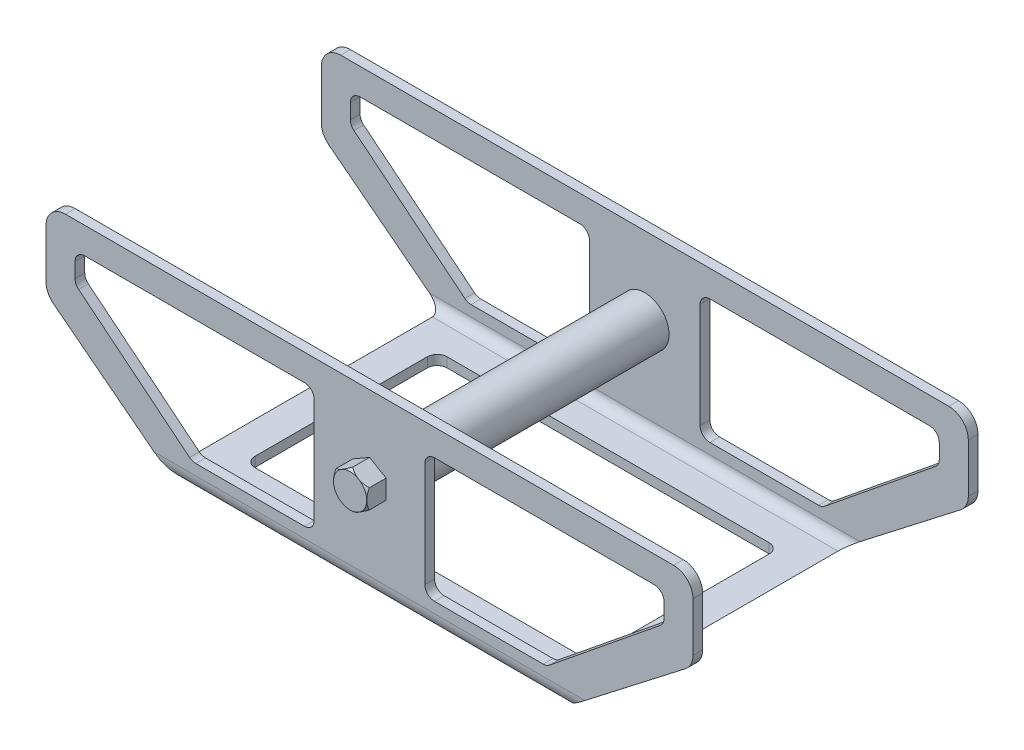
SolidWorks part; units mm, degrees
ref_plane "Front Plane" through (0, 0, 0) normal (0, 0, 1) x (1, 0, 0)
ref_plane "Top Plane" through (0, 0, 0) normal (0, 1, 0) x (1, 0, 0)
ref_plane "Right Plane" through (0, 0, 0) normal (1, 0, 0) x (0, 0, -1)
sketch "Sketch1" plane through (0, 0, 0) normal (0, 0, 1) x (1, 0, 0)
  line L0 (0, -413.3583) -> (0, 413.3583) construction
  line L1 (-333.43, 0) -> (333.43, 0)
  line L2 (333.43, 0) -> (333.43, -80.23)
  line L3 (333.43, -80.23) -> (196.11, -186.5035)
  line L4 (196.11, -186.5035) -> (-196.11, -186.5035)
  line L5 (-333.43, 0) -> (-333.43, -80.23)
  line L6 (-333.43, -80.23) -> (-196.11, -186.5035)
  point P13 (0, 0)
  point P15 (0, -186.5035)
  dimension "D1" = 333.43
  dimension "D2" = 80.23
  dimension "D3" = 173.64
  dimension "D4" = 196.11
extrude "Boss-Extrude1" add sketch "Sketch1" along normal mid plane 293.75
sketch "Sketch2" plane through (333.43, 0, 0) normal (1, 0, 0) x (0, 0, -1)
  line L0 (-146.875, -186.5035) -> (146.875, -186.5035) construction
  line L1 (-136.875, 36.7584) -> (136.875, 36.7584)
  line L2 (-136.875, 36.7584) -> (-136.875, -176.5035)
  line L3 (-136.875, -176.5035) -> (136.875, -176.5035)
  line L4 (136.875, 36.7584) -> (136.875, -176.5035)
  line L5 (-146.875, -186.5035) -> (-146.875, -80.23) construction
  line L6 (146.875, -186.5035) -> (146.875, -80.23) construction
  dimension "D1" = 10
  dimension "D2" = 10
  dimension "D3" = 10
extrude "Cut-Extrude1" cut sketch "Sketch2" against normal through all
fillet "Fillet1" radius 10 2 edges at (0, -176.5035, -136.875) (0, -176.5035, 136.875)
fillet "Fillet2" radius 20 2 edges at (0, -186.5035, 146.875) (0, -186.5035, -146.875)
sketch "Sketch3" plane through (0, 0, 136.875) normal (0, 0, -1) x (-1, 0, 0)
  circle A0 centre (0, -80.23) radius 25
  dimension "D1" = 50
extrude "Boss-Extrude2" add sketch "Sketch3" along normal up to surface (273.75 mm away) up to face at (0, -82.2445, -136.875)
sketch "Sketch4" plane through (0, 0, 146.875) normal (0, 0, 1) x (1, 0, 0)
  line L1 (0, -100.03) -> (17.1473, -90.13)
  line L2 (17.1473, -90.13) -> (17.1473, -70.33)
  line L3 (17.1473, -70.33) -> (0, -60.43)
  line L4 (0, -60.43) -> (-17.1473, -70.33)
  line L5 (-17.1473, -70.33) -> (-17.1473, -90.13)
  line L6 (-17.1473, -90.13) -> (0, -100.03)
  circle A2 centre (0, -80.23) radius 17.1473 construction
  dimension "D1" = 19.8
extrude "Boss-Extrude3" add sketch "Sketch4" along normal blind 20
sketch "Sketch5" plane through (0, 0, 166.875) normal (0, 0, 1) x (1, 0, 0)
  line L0 (-17.1473, -80.23) -> (17.1473, -80.23) construction
  line L1 (-17.1473, -70.33) -> (-17.1473, -90.13) construction
  line L2 (17.1473, -90.13) -> (17.1473, -70.33) construction
  line L3 (0, -60.43) -> (-17.1473, -70.33) construction
  circle A0 centre (0, -80.23) radius 17.1473
  circle A1 centre (0, -80.23) radius 51.1114
extrude "Cut-Extrude2" cut sketch "Sketch5" against normal blind 20 draft 45
mirror "Mirror1" about plane through (0, 0, 0) normal (0, 0, 1) of "Cut-Extrude2", "Boss-Extrude3"
sketch "Sketch6" plane through (0, 0, 146.875) normal (0, 0, 1) x (1, 0, 0)
  line L0 (0, 0) -> (0, -253.0542) construction
  line L1 (-303.5, -37.26) -> (-303.5, -52.66)
  line L2 (-299.7992, -60.4266) -> (-185.4192, -153.1966)
  line L3 (-179.12, -155.43) -> (-67, -155.43)
  line L4 (-57, -145.43) -> (-57, -37.26)
  line L5 (-67, -27.26) -> (-293.5, -27.26)
  line L7 (333.43, 0) -> (-333.43, 0) construction
  line L8 (-333.43, 0) -> (-333.43, -80.23) construction
  line L9 (57, -145.43) -> (57, -37.26)
  line L10 (179.12, -155.43) -> (67, -155.43)
  line L11 (299.7992, -60.4266) -> (185.4192, -153.1966)
  line L12 (303.5, -37.26) -> (303.5, -52.66)
  line L13 (67, -27.26) -> (293.5, -27.26)
  arc A0 (-57, -37.26) -> (-67, -27.26) centre (-67, -37.26) ccw
  arc A1 (-67, -155.43) -> (-57, -145.43) centre (-67, -145.43) ccw
  arc A2 (-185.4192, -153.1966) -> (-179.12, -155.43) centre (-179.12, -145.43) ccw
  arc A3 (-303.5, -52.66) -> (-299.7992, -60.4266) centre (-293.5, -52.66) ccw
  arc A4 (-303.5, -37.26) -> (-293.5, -27.26) centre (-293.5, -37.26) cw
  arc A5 (67, -155.43) -> (57, -145.43) centre (67, -145.43) cw
  arc A6 (185.4192, -153.1966) -> (179.12, -155.43) centre (179.12, -145.43) cw
  arc A7 (303.5, -52.66) -> (299.7992, -60.4266) centre (293.5, -52.66) cw
  arc A8 (57, -37.26) -> (67, -27.26) centre (67, -37.26) cw
  arc A9 (303.5, -37.26) -> (293.5, -27.26) centre (293.5, -37.26) ccw
  dimension "D1" = 10
  dimension "D2" = 226.5
  dimension "D3" = 108.17
  dimension "D4" = 112.12
  dimension "D5" = 15.4
  dimension "D6" = 27.26
  dimension "D7" = 29.93
extrude "Cut-Extrude3" cut sketch "Sketch6" against normal through all both and the other way through all
sketch "Sketch7" plane through (0, -186.5035, 0) normal (0, -1, 0) x (1, 0, 0)
  line L6 (196.11, 126.875) -> (196.11, -126.875) construction
  line L7 (166.11, 99) -> (-166.11, 99)
  line L8 (176.11, 89) -> (176.11, -89)
  line L9 (166.11, -99) -> (-166.11, -99)
  line L10 (-176.11, 89) -> (-176.11, -89)
  line L11 (176.11, 99) -> (-176.11, -99) construction
  line L12 (176.11, -99) -> (-176.11, 99) construction
  arc A0 (-166.11, 99) -> (-176.11, 89) centre (-166.11, 89) ccw
  arc A1 (176.11, -89) -> (166.11, -99) centre (166.11, -89) cw
  arc A2 (166.11, 99) -> (176.11, 89) centre (166.11, 89) cw
  arc A3 (-166.11, -99) -> (-176.11, -89) centre (-166.11, -89) cw
  point P0 (0, 0)
  dimension "D3" = 10
  dimension "D1" = 198
  dimension "D2" = 20
extrude "Cut-Extrude4" cut sketch "Sketch7" against normal up to surface (10 mm away) and the other way through all up to face at (0, -176.5035, 0)
fillet "Fillet3" radius 20 8 edges at (-333.43, -80.23, 141.875) (-333.43, 0, 141.875) (-333.43, -80.23, -141.875) (-333.43, 0, -141.875) (333.43, 0, 141.875) (333.43, -80.23, 141.875) (333.43, -80.23, -141.875) (333.43, 0, -141.875)
